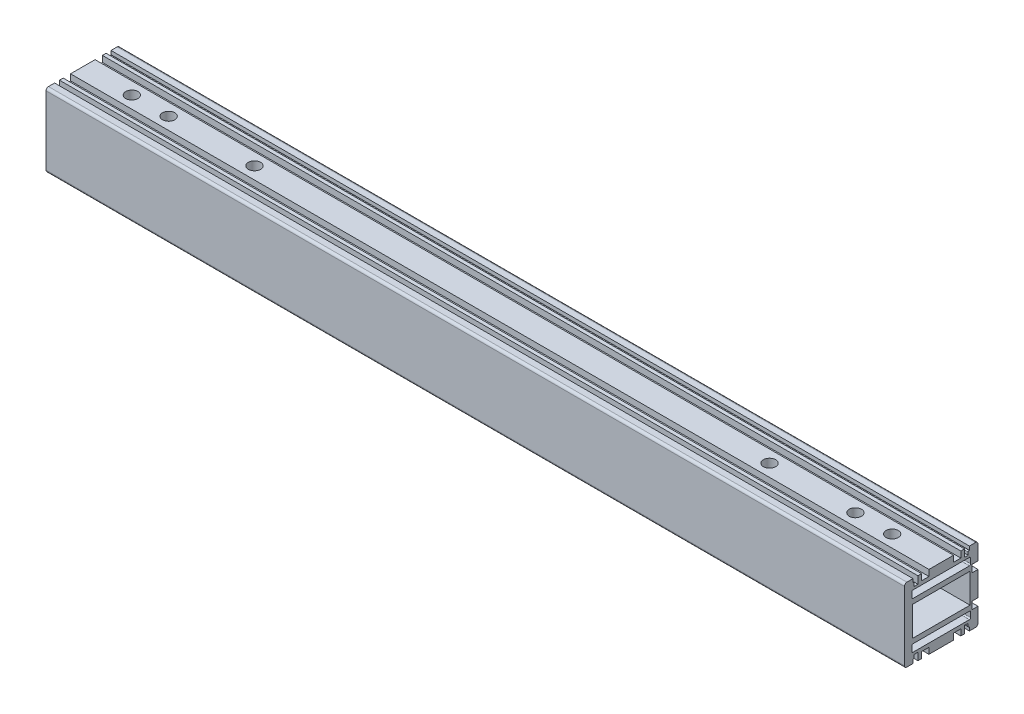
SolidWorks part; units mm, degrees
ref_plane "前视基准面" through (0, 0, 0) normal (0, 0, 1) x (1, 0, 0)
ref_plane "上视基准面" through (0, 0, 0) normal (0, 1, 0) x (1, 0, 0)
ref_plane "右视基准面" through (0, 0, 0) normal (1, 0, 0) x (0, 0, -1)
sketch "草图1" plane through (0, 0, 0) normal (1, 0, 0) x (0, 0, -1)
  line L0 (-15, 15) -> (15, -15) construction
  line L1 (-14, 15) -> (-11.5, 15)
  line L2 (-15, 14) -> (-15, -14)
  line L3 (-14, -15) -> (-11.5, -15)
  line L4 (15, 14) -> (15, 8)
  line L5 (15, 15) -> (-15, -15) construction
  line L6 (-11.5, 15) -> (-11.5, 13.5)
  line L7 (-11.5, 13.5) -> (-11.4, 13.5)
  line L8 (-11, 13.1) -> (-11, 12)
  line L9 (-11, 12) -> (-9.5, 12)
  line L10 (-9.5, 12) -> (-9.5, 15)
  line L11 (-9.5, 15) -> (-8, 15)
  line L12 (-8, 15) -> (-8, 12.5)
  line L13 (-8, 12.5) -> (-5, 12.5)
  line L14 (-5, 12.5) -> (-5, 15)
  line L15 (-5, 15) -> (5, 15)
  line L16 (0, 21.5201) -> (0, -18.309) construction
  line L17 (0, 55) -> (0, -55) construction
  line L18 (5, 12.5) -> (5, 15)
  line L19 (8, 12.5) -> (5, 12.5)
  line L20 (8, 15) -> (8, 12.5)
  line L21 (9.5, 15) -> (8, 15)
  line L22 (9.5, 12) -> (9.5, 15)
  line L23 (11, 12) -> (9.5, 12)
  line L24 (11, 13.1) -> (11, 12)
  line L25 (11.5, 13.5) -> (11.4, 13.5)
  line L26 (11.5, 15) -> (11.5, 13.5)
  line L27 (8, 15) -> (9.5, 15)
  line L28 (11.5, 15) -> (14, 15)
  line L29 (-19.8303, 0) -> (22.13, 0) construction
  line L30 (55, 0) -> (-55, 0) construction
  line L31 (8, -15) -> (9.5, -15)
  line L32 (11.5, -15) -> (11.5, -13.5)
  line L33 (11.5, -13.5) -> (11.4, -13.5)
  line L34 (11, -13.1) -> (11, -12)
  line L35 (11, -12) -> (9.5, -12)
  line L36 (9.5, -12) -> (9.5, -15)
  line L37 (9.5, -15) -> (8, -15)
  line L38 (8, -15) -> (8, -12.5)
  line L39 (8, -12.5) -> (5, -12.5)
  line L40 (5, -12.5) -> (5, -15)
  line L41 (-5, -15) -> (5, -15)
  line L42 (-5, -12.5) -> (-5, -15)
  line L43 (-8, -12.5) -> (-5, -12.5)
  line L44 (-8, -15) -> (-8, -12.5)
  line L45 (-9.5, -15) -> (-8, -15)
  line L46 (-9.5, -12) -> (-9.5, -15)
  line L47 (-11, -12) -> (-9.5, -12)
  line L48 (-11, -13.1) -> (-11, -12)
  line L49 (-11.5, -13.5) -> (-11.4, -13.5)
  line L50 (-11.5, -15) -> (-11.5, -13.5)
  line L51 (-9.5, -15) -> (-8, -15)
  line L52 (-5, -15) -> (5, -15)
  line L53 (8, -15) -> (9.5, -15)
  line L54 (11.5, -15) -> (14, -15)
  line L55 (15, 8) -> (12.5, 8)
  line L56 (12.5, 8) -> (12.5, 5)
  line L57 (12.5, 5) -> (15, 5)
  line L58 (12.5, -5) -> (15, -5)
  line L59 (12.5, -8) -> (12.5, -5)
  line L60 (15, -8) -> (12.5, -8)
  line L61 (15, 5) -> (15, -5)
  line L62 (15, -8) -> (15, -14)
  line L63 (12, -10.5) -> (12, -8.5)
  line L64 (-11.5, 11) -> (11.5, 11)
  line L65 (-12, 10.5) -> (-12, 8.5)
  line L66 (-11.5, 8) -> (11.5, 8)
  line L67 (12, 10.5) -> (12, 8.5)
  line L68 (-11.5, -8) -> (11.5, -8)
  line L69 (-12, -10.5) -> (-12, -8.5)
  line L70 (-11.5, -11) -> (11.5, -11)
  line L72 (-11.75, 6) -> (11.75, 6)
  line L73 (-11.75, 6) -> (-11.75, -6)
  line L74 (-11.75, -6) -> (11.75, -6)
  line L75 (11.75, 6) -> (11.75, -6)
  arc A0 (12, 8.5) -> (11.5, 8) centre (11.5, 8.5) cw
  arc A1 (11.5, 11) -> (12, 10.5) centre (11.5, 10.5) cw
  arc A2 (-11.5, 11) -> (-12, 10.5) centre (-11.5, 10.5) ccw
  arc A3 (-11.5, 8) -> (-12, 8.5) centre (-11.5, 8.5) cw
  arc A4 (-11, -13.1) -> (-11.4, -13.5) centre (-11.4, -13.1) cw
  arc A5 (11.4, -13.5) -> (11, -13.1) centre (11.4, -13.1) cw
  arc A6 (11.4, 13.5) -> (11, 13.1) centre (11.4, 13.1) ccw
  arc A7 (-11, 13.1) -> (-11.4, 13.5) centre (-11.4, 13.1) ccw
  arc A8 (-11.5, -8) -> (-12, -8.5) centre (-11.5, -8.5) ccw
  arc A9 (-11.5, -11) -> (-12, -10.5) centre (-11.5, -10.5) cw
  arc A10 (11.5, -11) -> (12, -10.5) centre (11.5, -10.5) ccw
  arc A11 (12, -8.5) -> (11.5, -8) centre (11.5, -8.5) ccw
  arc A12 (14, 15) -> (15, 14) centre (14, 14) cw
  arc A13 (14, -15) -> (15, -14) centre (14, -14) ccw
  arc A14 (-15, -14) -> (-14, -15) centre (-14, -14) ccw
  arc A15 (-15, 14) -> (-14, 15) centre (-14, 14) cw
  point P69 (12, 11)
  point P72 (-12, 11)
  point P77 (-11, -13.5)
  point P80 (11, -13.5)
  point P83 (11, 13.5)
  point P86 (-11, 13.5)
  point P99 (-12, -11)
  point P100 (12, -11)
  dimension "D17" = 0.5
  dimension "D18" = 0.4
  dimension "D21" = 1
  dimension "D1" = 3.5
  dimension "D2" = 1.5
  dimension "D3" = 0.5
  dimension "D4" = 1.5
  dimension "D5" = 3
  dimension "D6" = 30
  dimension "D7" = 30
  dimension "D8" = 1.5
  dimension "D9" = 2.5
  dimension "D10" = 3
  dimension "D11" = 2.5
  dimension "D12" = 7
  dimension "D13" = 3
  dimension "D14" = 4
  dimension "D15" = 3
  dimension "D16" = 24
  dimension "D19" = 23.5
  dimension "D20" = 12
extrude "凸台-拉伸1" add sketch "草图1" along normal mid plane 350 contours A15 L2 A14 L3 L50 L49 A4 L48 L47 L46 L45 L44 L43 L42 L41 L40 L39 L38 L31 L36 L35 L34 A5 L33 L32 L54 A13 L62 L60 L59 L58 L61 L57 L56 L55 L4 A12 L28 L26 L25 A6 L24 L23 L22 L21 L20 L19 L18 L15 L14 L13
hole_wizard "M6 螺纹孔1" positions "草图3" profile "草图2" tap size "M6" standard "GB"
sketch "草图3" plane through (0, 15, 0) normal (0, 1, 0) x (-1, 0, 0)
  line L0 (-175, 5) -> (-175, -5) construction
  line L1 (-175, 15) -> (175, 15) construction
  point P0 (-155, 0)
  point P1 (-140, 0)
  point P4 (140, 0)
  point P7 (155, 0)
  dimension "D1" = 20
  dimension "D2" = 15
sketch "草图2" plane through (155, 15, 0) normal (1, 0, 0) x (0, 0, 1)
  line L0 (0, 0) -> (0, 16.5022)
  line L1 (0, 16.5022) -> (2.5, 15)
  line L2 (2.5, 15) -> (2.5, 0)
  line L5 (2.5, 0) -> (0, 0)
  line L10 (0, 16.5022) -> (-2.5, 15) construction
  line L11 (0, -6.35) -> (0, 107.95) construction
  dimension "螺纹孔钻头直径" = 5
  dimension "螺纹孔钻头深度" = 15
  dimension "导头角度" = 118
cosmetic thread "孔螺蚊线1" parameters "D1"=9, "D2"=6
cosmetic thread "孔螺蚊线2" parameters "D1"=9, "D2"=6
cosmetic thread "孔螺蚊线3" parameters "D1"=9, "D2"=6
cosmetic thread "孔螺蚊线4" parameters "D1"=9, "D2"=6
hole_wizard "M6 螺纹孔2" positions "草图5" profile "草图4" tap size "M6" standard "GB"
sketch "草图5" plane through (0, -15, 0) normal (0, -1, 0) x (1, 0, 0)
  line L0 (175, 5) -> (175, -5) construction
  line L1 (175, -15) -> (-175, -15) construction
  point P0 (155, 0)
  point P1 (140, 0)
  point P4 (-140, 0)
  point P7 (-155, 0)
  dimension "D1" = 20
  dimension "D2" = 15
sketch "草图4" plane through (155, -15, 0) normal (1, 0, 0) x (0, 0, -1)
  line L0 (0, 0) -> (0, 16.5022)
  line L1 (0, 16.5022) -> (2.5, 15)
  line L2 (2.5, 15) -> (2.5, 0)
  line L5 (2.5, 0) -> (0, 0)
  line L10 (0, 16.5022) -> (-2.5, 15) construction
  line L11 (0, -6.35) -> (0, 107.95) construction
  dimension "螺纹孔钻头直径" = 5
  dimension "螺纹孔钻头深度" = 15
  dimension "导头角度" = 118
cosmetic thread "孔螺蚊线5" parameters "D1"=9, "D2"=6
cosmetic thread "孔螺蚊线6" parameters "D1"=9, "D2"=6
cosmetic thread "孔螺蚊线7" parameters "D1"=9, "D2"=6
cosmetic thread "孔螺蚊线8" parameters "D1"=9, "D2"=6
hole_wizard "M4 螺纹孔1" positions "草图7" profile "草图6" tap size "M4" standard "GB"
sketch "草图7" plane through (0, 0, -15) normal (0, 0, -1) x (-1, 0, 0)
  line L0 (-175, 15) -> (175, 15) construction
  line L1 (175, 14) -> (175, 8) construction
  point P1 (145, 0)
  point P3 (45, 0)
  point P5 (-55, 0)
  dimension "D1" = 15
  dimension "D2" = 100
  dimension "D3" = 100
  dimension "D4" = 30
sketch "草图6" plane through (-145, 0, -15) normal (1, 0, 0) x (0, 1, 0)
  line L0 (0, 0) -> (0, 11.0914)
  line L1 (0, 11.0914) -> (1.65, 10.1)
  line L2 (1.65, 10.1) -> (1.65, 0)
  line L5 (1.65, 0) -> (0, 0)
  line L10 (0, 11.0914) -> (-1.65, 10.1) construction
  line L11 (0, -6.35) -> (0, 107.95) construction
  dimension "螺纹孔钻头直径" = 3.3
  dimension "螺纹孔钻头深度" = 10.1
  dimension "导头角度" = 118
cosmetic thread "孔螺蚊线9" parameters "D1"=3.25, "D2"=4
cosmetic thread "孔螺蚊线10" parameters "D1"=3.25, "D2"=4
cosmetic thread "孔螺蚊线11" parameters "D1"=3.25, "D2"=4
hole_wizard "M6 螺纹孔3" positions "草图9" profile "草图8" tap size "M6" standard "GB"
sketch "草图9" plane through (0, 15, 0) normal (0, 1, 0) x (-1, 0, 0)
  line L0 (-175, -15) -> (175, -15) construction
  line L1 (175, 5) -> (175, -5) construction
  line L2 (-175, 5) -> (-175, -5) construction
  point P1 (105, 0)
  point P3 (-105, 0)
  dimension "D1" = 15
  dimension "D2" = 15
  dimension "D3" = 70
  dimension "D4" = 70
sketch "草图8" plane through (-105, 15, 0) normal (1, 0, 0) x (0, 0, 1)
  line L0 (0, 0) -> (0, 16.5022)
  line L1 (0, 16.5022) -> (2.5, 15)
  line L2 (2.5, 15) -> (2.5, 0)
  line L5 (2.5, 0) -> (0, 0)
  line L10 (0, 16.5022) -> (-2.5, 15) construction
  line L11 (0, -6.35) -> (0, 107.95) construction
  dimension "螺纹孔钻头直径" = 5
  dimension "螺纹孔钻头深度" = 15
  dimension "导头角度" = 118
cosmetic thread "孔螺蚊线12" parameters "D1"=9, "D2"=6
cosmetic thread "孔螺蚊线13" parameters "D1"=9, "D2"=6
